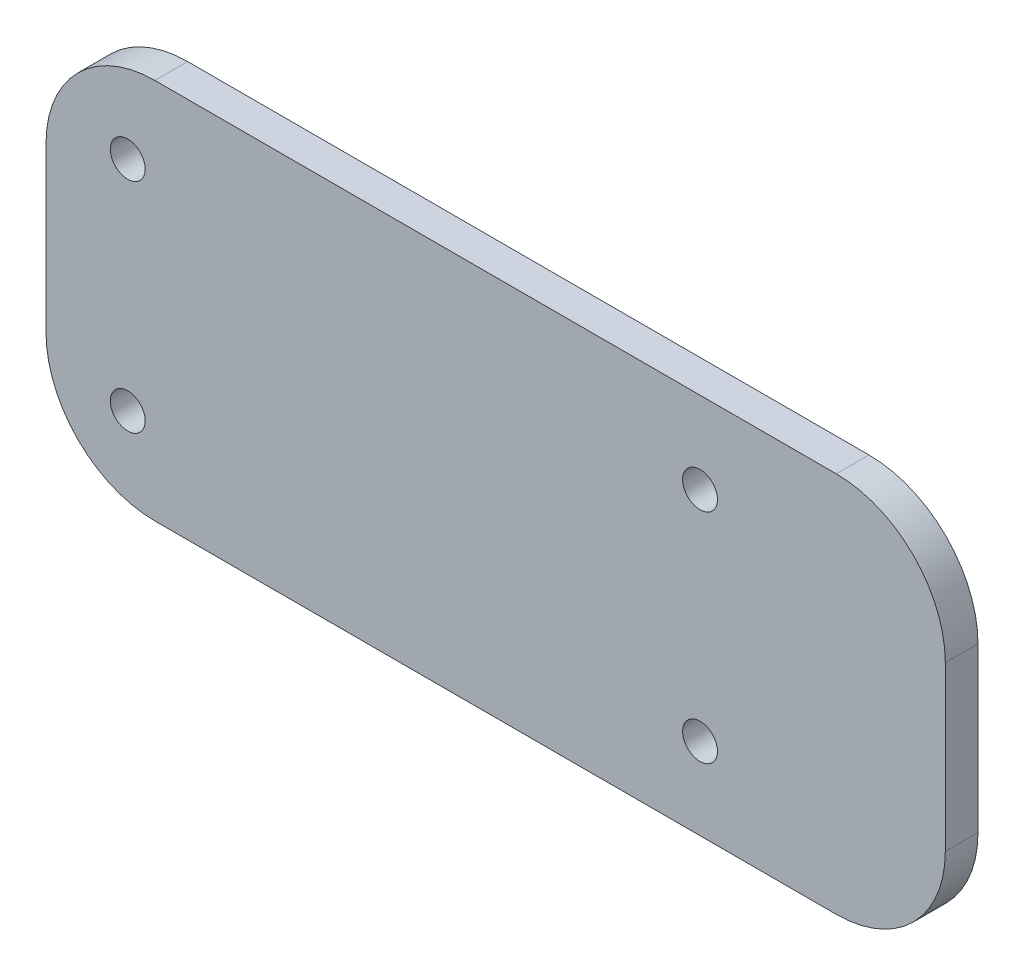
SolidWorks part; units mm, degrees
ref_plane "前视基准面" through (0, 0, 0) normal (0, 0, 1) x (1, 0, 0)
ref_plane "上视基准面" through (0, 0, 0) normal (0, 1, 0) x (1, 0, 0)
ref_plane "右视基准面" through (0, 0, 0) normal (1, 0, 0) x (0, 0, -1)
sketch "草图1" plane through (0, 0, 0) normal (0, 0, 1) x (1, 0, 0)
  line L0 (33.75, 17.5) -> (48.75, 17.5)
  line L1 (-33.75, -17.5) -> (33.75, -17.5)
  line L2 (-33.75, -17.5) -> (-33.75, 17.5)
  line L3 (-33.75, 17.5) -> (33.75, 17.5)
  line L4 (33.75, -17.5) -> (33.75, 17.5) construction
  line L5 (-33.75, -17.5) -> (33.75, 17.5) construction
  line L6 (-33.75, 17.5) -> (33.75, -17.5) construction
  line L7 (-26.25, -10) -> (26.25, -10) construction
  line L8 (-26.25, -10) -> (-26.25, 10) construction
  line L9 (-26.25, 10) -> (26.25, 10) construction
  line L10 (26.25, -10) -> (26.25, 10) construction
  line L11 (-26.25, -10) -> (26.25, 10) construction
  line L12 (-26.25, 10) -> (26.25, -10) construction
  line L13 (48.75, 17.5) -> (48.75, -17.5)
  line L14 (48.75, -17.5) -> (33.75, -17.5)
  circle A0 centre (-26.25, 10) radius 1.6
  circle A1 centre (-26.25, -10) radius 1.6
  circle A2 centre (26.25, -10) radius 1.6
  circle A3 centre (26.25, 10) radius 1.6
  point P0 (0, 0)
  point P6 (0, 0)
  dimension "D1" = 3.2
  dimension "D4" = 7.5
  dimension "D5" = 7.5
  dimension "D2" = 52.5
  dimension "D3" = 20
  dimension "D6" = 15
extrude "凸台-拉伸1" add sketch "草图1" along normal blind 3
fillet "圆角1" radius 10 4 edges at (-33.75, -17.5, 1.5) (-33.75, 17.5, 1.5) (48.75, 17.5, 1.5) (48.75, -17.5, 1.5)
